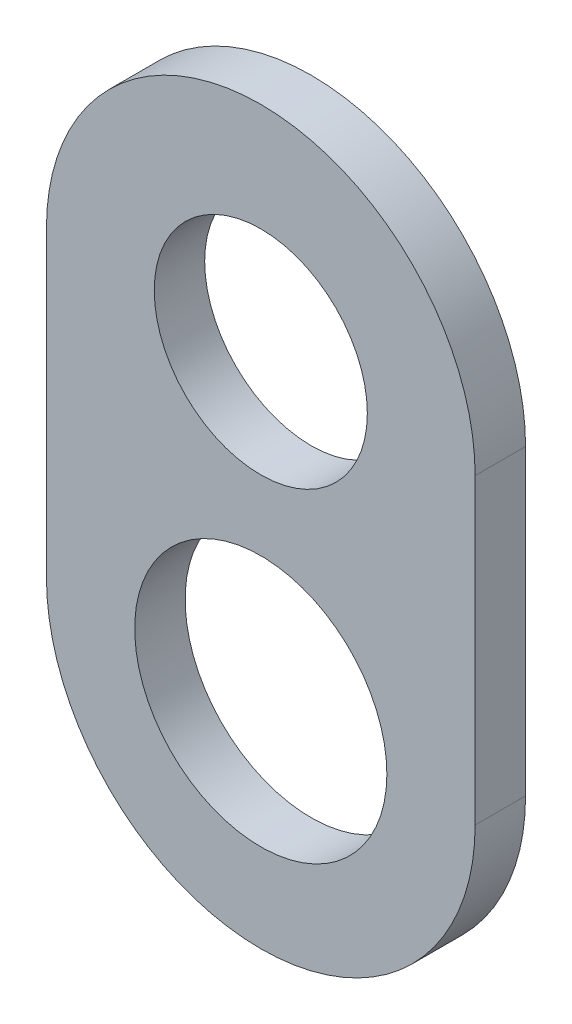
SolidWorks part; units mm, degrees
material "6061-T6 (SS)"
ref_plane "Front Plane" through (0, 0, 0) normal (0, 0, 1) x (1, 0, 0)
ref_plane "Top Plane" through (0, 0, 0) normal (0, 1, 0) x (1, 0, 0)
ref_plane "Right Plane" through (0, 0, 0) normal (1, 0, 0) x (0, 0, -1)
sketch "Sketch1" plane through (0, 0, 0) normal (0, 0, 1) x (1, 0, 0)
  line L0 (0, -30.48) -> (0, 0) construction
  line L1 (-21.59, -30.48) -> (-21.59, 0)
  line L2 (21.59, -30.48) -> (21.59, 0)
  circle A0 centre (0, 0) radius 10.7315
  circle A1 centre (0, -30.48) radius 12.7
  arc A2 (-21.59, -30.48) -> (21.59, -30.48) centre (0, -30.48) ccw
  arc A3 (21.59, 0) -> (-21.59, 0) centre (0, 0) ccw
  point P5 (0, -15.24)
  dimension "D1" = 21.463
  dimension "D2" = 25.4
  dimension "D3" = 8.89
  dimension "D4" = 30.48
extrude "Boss-Extrude1" add sketch "Sketch1" along normal blind 5.08
equation "\"F\"= 500"
equation "\"StressY\"= 40000"
equation "\"SF\"= 4"
equation "\"A\"= ( \"F\" * \"SF\" ) / ( \"StressY\" )"
equation "\"w\"= \"A\" / 0.2"
equation "\"th\"= \"A\" / 0.25"
equation "\"D3@Sketch1\"=.35"
equation "\"D1@Boss-Extrude1\"=\"th\""
